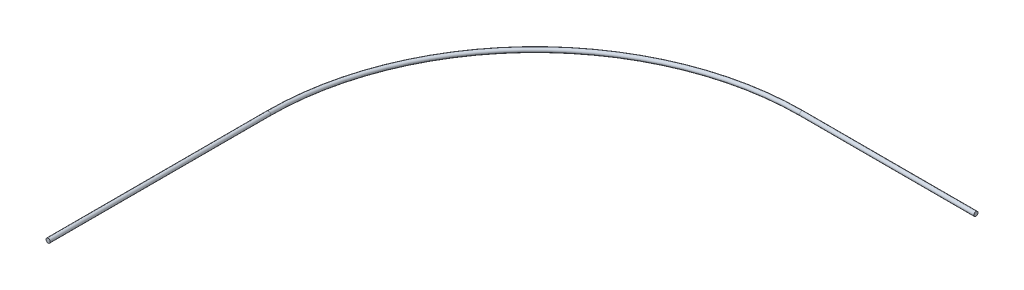
SolidWorks part; units mm, degrees
ref_plane "Front Plane" through (0, 0, 0) normal (0, 0, 1) x (1, 0, 0)
ref_plane "Top Plane" through (0, 0, 0) normal (0, 1, 0) x (1, 0, 0)
ref_plane "Right Plane" through (0, 0, 0) normal (1, 0, 0) x (0, 0, -1)
sketch "Sketch1" plane through (0, 0, 0) normal (0, 1, 0) x (1, 0, 0)
  line L0 (0, 0) -> (0, 2.1)
  line L1 (2.54, 4.64) -> (4.2, 4.64)
  arc A0 (0, 2.1) -> (2.54, 4.64) centre (2.54, 2.1) cw
  dimension "D1" = 2.54
  dimension "D2" = 2.1
  dimension "D3" = 4.2
sketch "Sketch3" plane through (0, 0, 0) normal (0, 0, 1) x (1, 0, 0)
  circle A0 centre (0, 0) radius 0.02
  dimension "D1" = 0.04
sweep "Sweep1" add profiles "Sketch3" path "Sketch1"
